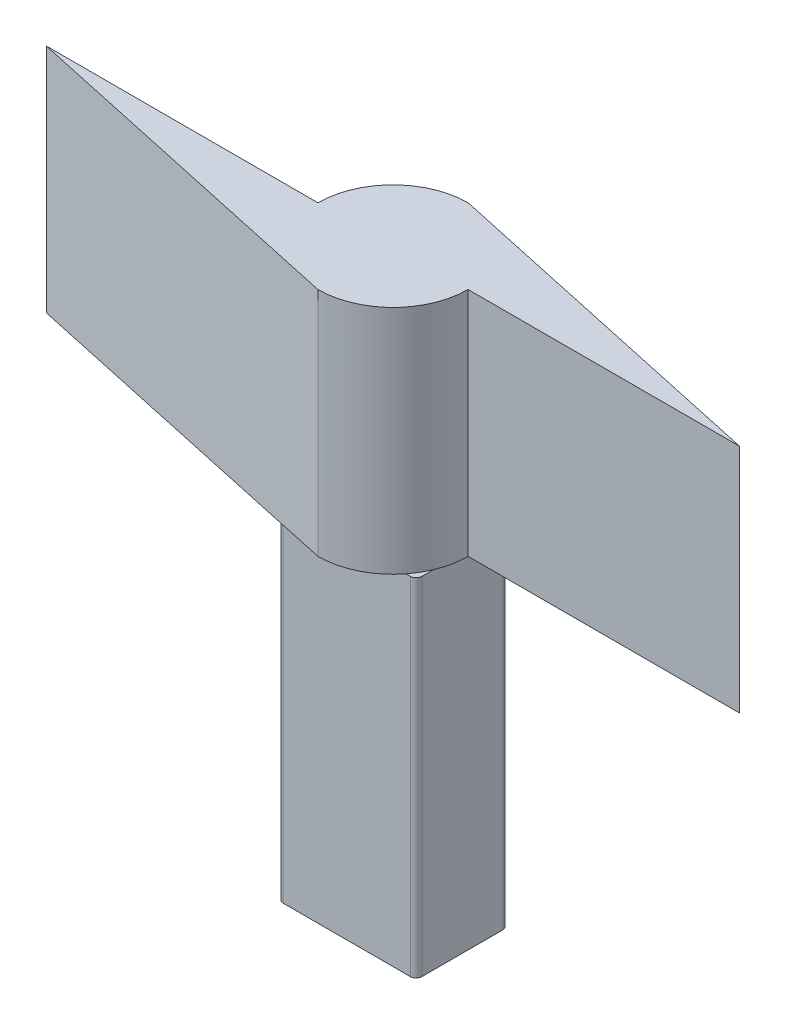
SolidWorks part; units mm, degrees
ref_plane "Alzado" through (0, 0, 0) normal (0, 0, 1) x (1, 0, 0)
ref_plane "Planta" through (0, 0, 0) normal (0, 1, 0) x (1, 0, 0)
ref_plane "Vista lateral" through (0, 0, 0) normal (1, 0, 0) x (0, 0, -1)
sketch "Croquis1" plane through (0, 0, 0) normal (0, 1, 0) x (1, 0, 0)
  line L0 (-2.5, 1.5) -> (2.5, 1.5)
  line L1 (-2.75, -2) -> (2.75, -2)
  line L2 (-3, -1.75) -> (-3, 1.75)
  line L3 (-2.75, 2) -> (2.75, 2)
  line L4 (3, -1.75) -> (3, 1.75)
  line L5 (-3, -2) -> (3, 2) construction
  line L6 (-3, 2) -> (3, -2) construction
  line L7 (2.5, -1.5) -> (2.5, 1.5)
  line L8 (-2.5, -1.5) -> (2.5, -1.5)
  line L9 (-2.5, -1.5) -> (-2.5, 1.5)
  line L10 (-3, -2) -> (3, -2) construction
  line L11 (-3, -2) -> (-3, 2) construction
  line L12 (3, -2) -> (3, 2) construction
  line L13 (-3, 2) -> (3, 2) construction
  arc A0 (-2.75, -2) -> (-3, -1.75) centre (-2.75, -1.75) cw
  arc A1 (2.75, -2) -> (3, -1.75) centre (2.75, -1.75) ccw
  arc A2 (2.75, 2) -> (3, 1.75) centre (2.75, 1.75) cw
  arc A3 (-3, 1.75) -> (-2.75, 2) centre (-2.75, 1.75) cw
  point P0 (0, 0)
  dimension "D4" = 0.25
  dimension "D1" = 6
  dimension "D2" = 4
  dimension "D3" = 0.5
extrude "Saliente-Extruir1" add sketch "Croquis1" along normal blind 15
sketch "Croquis2" plane through (0, 15, 0) normal (0, 1, 0) x (1, 0, 0)
  line L0 (-3.25, 0) -> (-15, 0)
  line L1 (-15, 0) -> (0, -3.25)
  line L3 (3.25, 0) -> (15, 0)
  line L4 (15, 0) -> (0, 3.25)
  arc A0 (0, -3.25) -> (3.25, 0) centre (0, 0) ccw
  arc A1 (0, 3.25) -> (-3.25, 0) centre (0, 0) ccw
  dimension "D1" = 6.5
  dimension "D2" = 15
  dimension "D3" = 15
extrude "Saliente-Extruir2" add sketch "Croquis2" along normal blind 10
